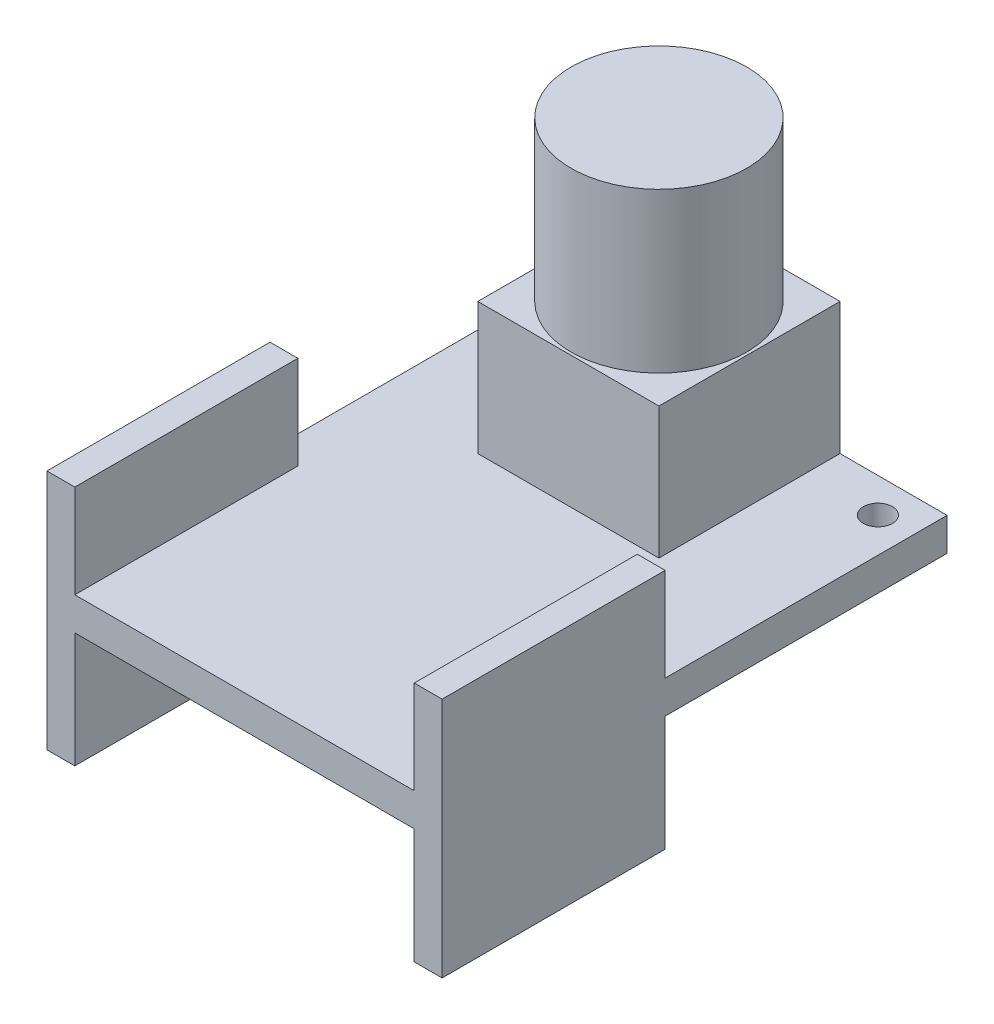
SolidWorks part; units mm, degrees
ref_plane "前视基准面" through (0, 0, 0) normal (0, 0, 1) x (1, 0, 0)
ref_plane "上视基准面" through (0, 0, 0) normal (0, 1, 0) x (1, 0, 0)
ref_plane "右视基准面" through (0, 0, 0) normal (1, 0, 0) x (0, 0, -1)
other "Configuration Table"
sketch "草图1" plane through (0, 0, 0) normal (0, 1, 0) x (1, 0, 0)
  line L1 (-18, -23) -> (18, -23)
  line L2 (-18, -23) -> (-18, 23)
  line L3 (-18, 23) -> (18, 23)
  line L4 (18, -23) -> (18, 23)
  line L5 (-18, -23) -> (18, 23) construction
  line L6 (-18, 23) -> (18, -23) construction
  point P0 (0, 0)
  dimension "D1" = 46
  dimension "D2" = 36
extrude "凸台-拉伸1" add sketch "草图1" along normal blind 3
sketch "草图2" plane through (0, 3, 0) normal (0, 1, 0) x (1, 0, 0)
  line L0 (0, 0) -> (28.9688, 0) construction
  line L1 (0, 0) -> (0, 24.9772) construction
  line L2 (18, -23) -> (18, -2.68)
  line L3 (18, -23) -> (18, 23) construction
  line L4 (18, -2.68) -> (15.46, -2.68)
  line L5 (15.46, -2.68) -> (15.46, -23)
  line L6 (-18, -23) -> (18, -23) construction
  line L7 (15.46, -23) -> (18, -23)
  line L8 (-15.46, -2.68) -> (-15.46, -23)
  line L9 (-18, -2.68) -> (-15.46, -2.68)
  line L10 (-18, -23) -> (-18, -2.68)
  line L11 (-15.46, -23) -> (-18, -23)
  line L12 (18, 23) -> (-18, 23) construction
  line L13 (-8.25, 6.5) -> (8.25, 6.5)
  line L14 (-8.25, 6.5) -> (-8.25, 23)
  line L15 (-8.25, 23) -> (8.25, 23)
  line L16 (8.25, 6.5) -> (8.25, 23)
  line L17 (-8.25, 6.5) -> (8.25, 23) construction
  line L18 (-8.25, 23) -> (8.25, 6.5) construction
  point P17 (0, 14.75)
  dimension "D1" = 2.54
  dimension "D2" = 20.32
  dimension "D3" = 16.5
  dimension "D4" = 16.5
extrude "凸台-拉伸2" add sketch "草图2" along normal blind 8.5 and the other way blind 13.5
sketch "草图3" plane through (0, 11.5, 0) normal (0, 1, 0) x (1, 0, 0)
  line L4 (8.25, 6.5) -> (8.25, 23)
  line L5 (8.25, 23) -> (-8.25, 23)
  line L6 (-8.25, 23) -> (-8.25, 6.5)
  line L7 (-8.25, 6.5) -> (8.25, 6.5)
  line L8 (8.25, 6.5) -> (8.25, 23)
  line L9 (8.25, 23) -> (-8.25, 23)
  line L10 (-8.25, 23) -> (-8.25, 6.5)
  line L11 (-8.25, 6.5) -> (8.25, 6.5)
  dimension "D1" = 0
extrude "凸台-拉伸3" add sketch "草图3" along normal blind 3.5
sketch "草图4" plane through (0, 15, 0) normal (0, 1, 0) x (1, 0, 0)
  line L0 (8.25, 23) -> (-8.25, 23) construction
  line L1 (8.25, 6.5) -> (8.25, 23) construction
  circle A0 centre (0, 14.75) radius 8
  dimension "D1" = 16
  dimension "D2" = 8.25
  dimension "D3" = 8.25
extrude "凸台-拉伸4" add sketch "草图4" along normal blind 14.5
sketch "草图5" plane through (0, 3, 0) normal (0, 1, 0) x (1, 0, 0)
  line L0 (0, 0) -> (0, 24.6904) construction
  line L1 (-8.25, 23) -> (-18, 23) construction
  circle A0 centre (-14.825, 19.875) radius 1.325
  circle A1 centre (14.825, 19.875) radius 1.325
  dimension "D1" = 29.65
  dimension "D2" = 2.65
  dimension "D3" = 3.125
extrude "切除-拉伸1" cut sketch "草图5" against normal blind 14.5
sketch "草图7" plane through (-8.25, 0, 0) normal (-1, 0, 0) x (0, 0, 1)
  line L4 (-6.5, -10.5) -> (-6.5, 0)
  line L5 (-6.5, 0) -> (-23, 0)
  line L6 (-23, 0) -> (-23, -10.5)
  line L7 (-23, -10.5) -> (-6.5, -10.5)
  line L8 (-6.5, -10.5) -> (-6.5, 0)
  line L9 (-6.5, 0) -> (-23, 0)
  line L10 (-23, 0) -> (-23, -10.5)
  line L11 (-23, -10.5) -> (-6.5, -10.5)
  dimension "D1" = 0
extrude "切除-拉伸2" cut sketch "草图7" against normal blind 31.5
